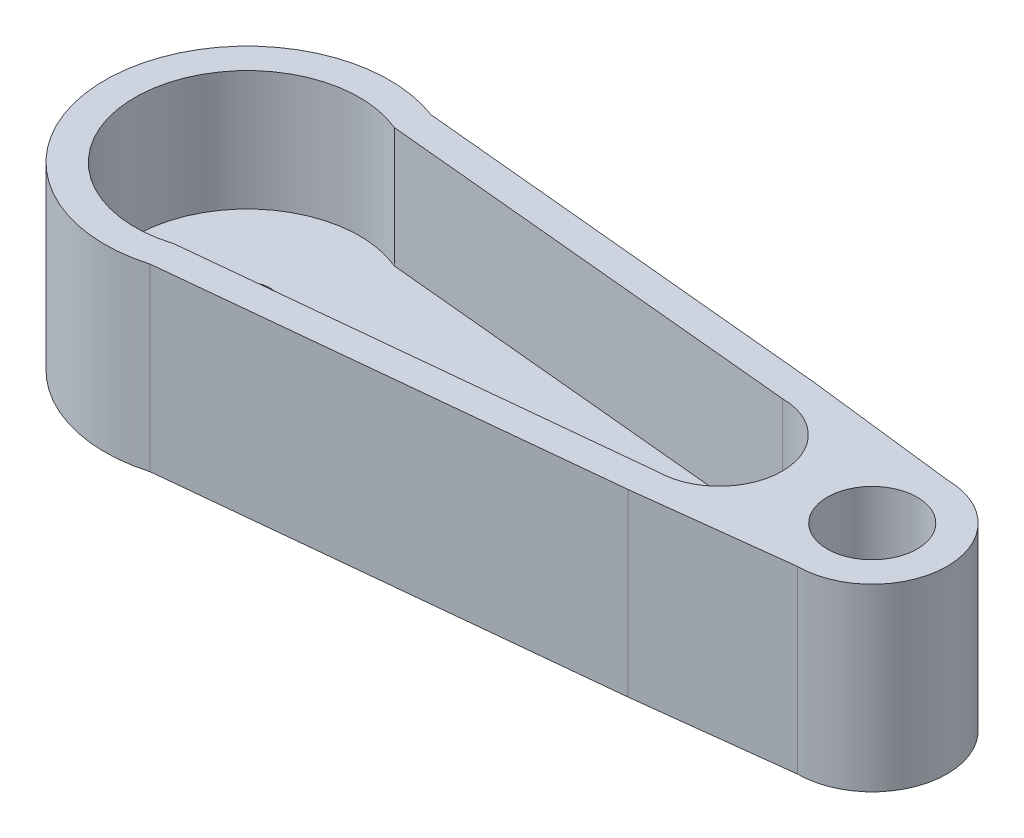
SolidWorks part; units mm, degrees
ref_plane "Front Plane" through (0, 0, 0) normal (0, 0, 1) x (1, 0, 0)
ref_plane "Top Plane" through (0, 0, 0) normal (0, 1, 0) x (1, 0, 0)
ref_plane "Right Plane" through (0, 0, 0) normal (1, 0, 0) x (0, 0, -1)
sketch "Sketch2" plane through (0, 0, 0) normal (0, 1, 0) x (1, 0, 0)
  line L0 (0, 0) -> (30, 0)
  line L1 (30, 0) -> (30, 10)
  line L2 (30, 10) -> (0, 10)
  line L3 (0, 10) -> (0, 0)
  line L4 (0, 5) -> (4.5, 5) construction
  line L5 (30, 5) -> (27.25, 5) construction
  dimension "D1" = 30
  dimension "D2" = 10
  dimension "D3" = 4.5
  dimension "D5" = 2.75
extrude "Boss-Extrude3" add sketch "Sketch2" along normal blind 6
sketch "Sketch3" plane through (0, 6, 0) normal (0, 1, 0) x (1, 0, 0)
  line L0 (0, 5) -> (5, 5) construction
  line L1 (0, 10) -> (0, 0) construction
  line L2 (30, 5) -> (22.25, 5) construction
  line L3 (30, 0) -> (30, 10) construction
  line L4 (-995.5, 5) -> (5, 5) construction
  line L5 (5, 5) -> (7.6517, 2.3483) construction
  line L7 (6.5447, 9.4538) -> (20.8446, 8.0955) construction
  line L8 (6.1277, 1.4236) -> (20.75, 2.9)
  line L9 (6.4501, 8.4583) -> (20.75, 7.1)
  line L10 (6.6872, 9.4403) -> (20.802, 8.0996)
  line L11 (6.3243, 0.4383) -> (20.8052, 1.9005)
  line L12 (22.25, 5) -> (1027.05, 5) construction
  line L13 (6.2282, 0.4286) -> (20.8505, 1.9051) construction
  arc A0 (6.4501, 8.4583) -> (6.1277, 1.4236) centre (5, 5) ccw
  arc A2 (20.75, 2.9) -> (20.75, 7.1) centre (20.75, 5) ccw
  arc A3 (6.6872, 9.4403) -> (6.3243, 0.4383) centre (5, 5) ccw
  arc A4 (20.8052, 1.9005) -> (20.802, 8.0996) centre (20.75, 5) ccw
  circle A5 centre (5, 5) radius 4.75 construction
  arc A6 (8.3588, 1.6412) -> (8.3672, 1.6497) centre (5, 5) ccw
  circle A7 centre (20.75, 5) radius 3.1 construction
  circle A8 centre (20.75, 5) radius 2.1 construction
  circle A9 centre (5, 5) radius 3.75 construction
  dimension "D3" = 7.5
  dimension "D2" = 4.2
  dimension "D1" = 5
  dimension "D5" = 45
  dimension "D7" = 1
  dimension "D8" = 1
  dimension "D9" = 1
  dimension "D10" = 1
extrude "Cut-Extrude2" cut sketch "Sketch3" against normal blind 4 contours L9 A2 L8 A0
sketch "Sketch5" plane through (0, 6, 0) normal (0, 1, 0) x (1, 0, 0)
  line L0 (20.802, 8.0996) -> (25.85, 7.5016)
  line L1 (25.85, 2.5016) -> (20.8052, 1.9005)
  line L2 (23.85, 5.0016) -> (25.85, 5.0016) construction
  line L4 (6.3243, 0.4383) -> (20.8052, 1.9005)
  line L5 (20.802, 8.0996) -> (6.6872, 9.4403)
  line L6 (6.3243, 0.4383) -> (20.8052, 1.9005)
  line L7 (20.802, 8.0996) -> (6.6872, 9.4403)
  line L8 (0, 10) -> (30, 10)
  line L9 (0, 10) -> (0, 0)
  line L10 (0, 0) -> (30, 0)
  line L11 (30, 10) -> (30, 0)
  circle A2 centre (25.85, 5.0016) radius 1.5
  arc A3 (25.85, 2.5016) -> (25.85, 7.5016) centre (25.85, 5.0016) ccw
  arc A4 (20.8052, 1.9005) -> (20.802, 8.0996) centre (20.75, 5) ccw
  arc A5 (6.6872, 9.4403) -> (6.3243, 0.4383) centre (5, 5) ccw
  arc A7 (6.6872, 9.4403) -> (6.3243, 0.4383) centre (5, 5) ccw
  dimension "D3" = 3
  dimension "D4" = 5
  dimension "D2" = 2
  dimension "D1" = 1
extrude "Cut-Extrude3" cut sketch "Sketch5" against normal through all contours L10 L5 L8 L9 A7 L7 L0 A3 L1 L6
sketch "Sketch6" plane through (0, 6, 0) normal (0, 1, 0) x (1, 0, 0)
  circle A0 centre (25.85, 5.0016) radius 1.5
  dimension "D1" = 3
extrude "Cut-Extrude4" cut sketch "Sketch6" against normal through all
sketch "Sketch7" plane through (0, 2, 0) normal (0, 1, 0) x (1, 0, 0)
  circle A0 centre (5, 5) radius 0.75
  dimension "D1" = 1.5
extrude "Cut-Extrude5" cut sketch "Sketch7" against normal through all
